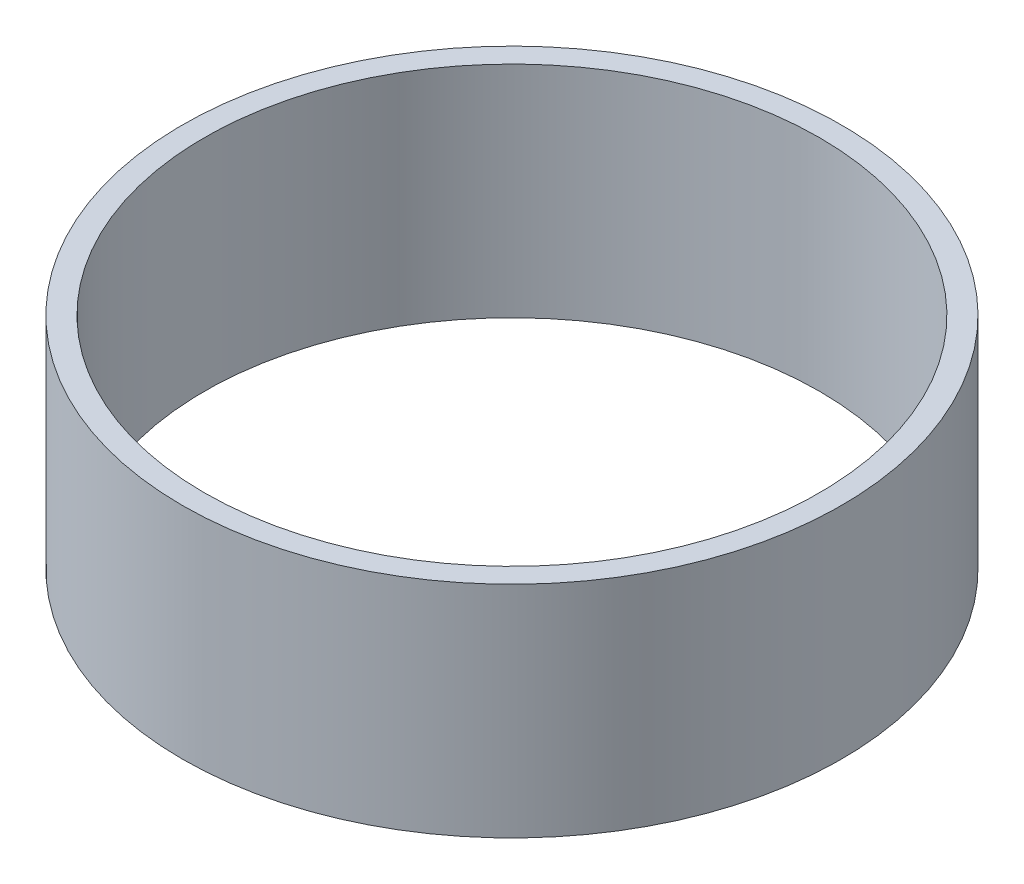
SolidWorks part; units mm, degrees
material "1060 Alloy"
ref_plane "Front" through (0, 0, 0) normal (0, 0, 1) x (1, 0, 0)
ref_plane "Top" through (0, 0, 0) normal (0, 1, 0) x (1, 0, 0)
ref_plane "Right" through (0, 0, 0) normal (1, 0, 0) x (0, 0, -1)
sketch "Sketch1" plane through (0, 0, 0) normal (0, 1, 0) x (1, 0, 0)
  circle A0 centre (0, 0) radius 35
  circle A1 centre (0, 0) radius 37.5
  dimension "D1" = 70
  dimension "D2" = 75
extrude "Boss-Extrude1" add sketch "Sketch1" along normal blind 25
